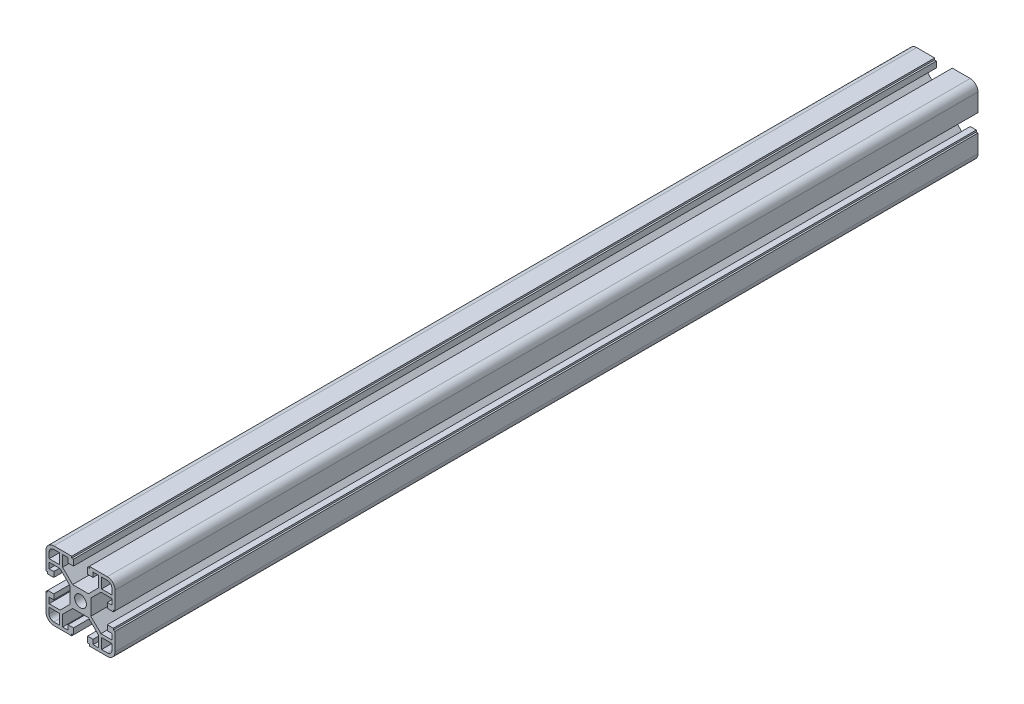
SolidWorks part; units mm, degrees
material "6063-T5"
ref_plane "Front Plane" through (0, 0, 0) normal (0, 0, 1) x (1, 0, 0)
ref_plane "Top Plane" through (0, 0, 0) normal (0, 1, 0) x (1, 0, 0)
ref_plane "Right Plane" through (0, 0, 0) normal (1, 0, 0) x (0, 0, -1)
sketch "Sketch3" plane through (0, 0, 0) normal (0, 0, 1) x (1, 0, 0)
  line L0 (17.9333, 92.7) -> (169.2667, 92.7) construction
  line L1 (-6, 6) -> (6, 6)
  line L2 (-6, 6) -> (-6, -6)
  line L3 (-6, -6) -> (6, -6)
  line L4 (6, 6) -> (6, -6)
  line L5 (0, 0) -> (20.1249, 20.1249) construction
  line L6 (4.5736, 4.5736) -> (11.4537, 11.4537) construction
  line L7 (5.2807, 3.8665) -> (12.0153, 10.6011)
  line L8 (3.8665, 5.2807) -> (10.7858, 12.2)
  line L13 (11.8142, 10.4) -> (18.2, 10.4)
  line L14 (6, 0) -> (23.1042, 0) construction
  line L15 (0, 6) -> (0, 13.9346) construction
  line L16 (4.5736, 4.5736) -> (11.8129, 11.8129) construction
  line L17 (5.2807, 3.8665) -> (12.52, 11.1058) construction
  line L18 (3.8665, 5.2807) -> (11.1058, 12.52) construction
  line L19 (10.4, 11.8142) -> (10.4, 18.2)
  line L20 (10.4, 18.2) -> (7.2581, 18.2)
  line L21 (-20, 20) -> (20, 20) construction
  line L22 (-20, 20) -> (-20, -20) construction
  line L23 (-20, -20) -> (20, -20) construction
  line L24 (20, 20) -> (20, -20) construction
  line L25 (7.2581, 18.2) -> (7.2581, 15.5)
  line L26 (7.2581, 15.5) -> (4.1, 15.5)
  line L27 (4.1, 15.5) -> (4.1, 19)
  line L28 (4.1, 19) -> (5.1, 19)
  line L29 (5.1, 19) -> (5.1, 20)
  line L30 (5.1, 20) -> (15.5, 20)
  line L31 (20, 15.5) -> (20, 5.1)
  line L32 (20, 5.1) -> (19, 5.1)
  line L33 (19, 5.1) -> (19, 4.1)
  line L34 (19, 4.1) -> (15.5, 4.1)
  line L35 (15.5, 4.1) -> (15.5, 7.1)
  line L36 (15.5, 7.1) -> (18.2, 7.1)
  line L37 (18.2, 7.1) -> (18.2, 10.4)
  line L42 (18.2, 12.2) -> (12.2, 12.2)
  line L43 (12.2, 18.2) -> (12.2, 18.2)
  line L44 (12.2, 18.2) -> (12.2, 18.2)
  line L45 (12.2, 18.2) -> (12.2, 18.2)
  line L46 (12.2, 18.2) -> (12.2, 18.2)
  line L47 (12.2, 18.2) -> (12.2, 18.2)
  line L48 (12.2, 18.2) -> (12.2, 18.2)
  line L49 (12.2, 18.2) -> (15.5, 18.2)
  line L50 (18.2, 15.5) -> (18.2, 12.2)
  line L51 (18.2, 12.2) -> (18.2, 12.2)
  line L52 (18.2, 12.2) -> (18.2, 12.2)
  line L53 (18.2, 12.2) -> (18.2, 12.2)
  line L54 (18.2, 12.2) -> (18.2, 12.2)
  line L55 (18.2, 12.2) -> (18.2, 12.2)
  line L56 (18.2, 12.2) -> (18.2, 12.2)
  line L57 (12.2, 12.2) -> (12.2, 18.2)
  line L58 (11.8142, 12.2) -> (18.2, 12.2) construction
  line L59 (12.2, 11.8142) -> (12.2, 18.2) construction
  line L60 (-18.2, 15.5) -> (-18.2, 12.2)
  line L61 (-12.2, 18.2) -> (-15.5, 18.2)
  line L62 (-12.2, 12.2) -> (-12.2, 18.2)
  line L63 (-18.2, 12.2) -> (-12.2, 12.2)
  line L64 (-11.8142, 10.4) -> (-18.2, 10.4)
  line L65 (-18.2, 7.1) -> (-18.2, 10.4)
  line L66 (-15.5, 7.1) -> (-18.2, 7.1)
  line L67 (-15.5, 4.1) -> (-15.5, 7.1)
  line L68 (-19, 4.1) -> (-15.5, 4.1)
  line L69 (-19, 5.1) -> (-19, 4.1)
  line L70 (-20, 5.1) -> (-19, 5.1)
  line L71 (-20, 15.5) -> (-20, 5.1)
  line L72 (-5.1, 20) -> (-15.5, 20)
  line L73 (-5.1, 19) -> (-5.1, 20)
  line L74 (-4.1, 19) -> (-5.1, 19)
  line L75 (-4.1, 15.5) -> (-4.1, 19)
  line L76 (-7.2581, 15.5) -> (-4.1, 15.5)
  line L77 (-7.2581, 18.2) -> (-7.2581, 15.5)
  line L78 (-10.4, 18.2) -> (-7.2581, 18.2)
  line L79 (-10.4, 11.8142) -> (-10.4, 18.2)
  line L80 (-10.4, 11.8142) -> (-4.5858, 6)
  line L81 (-11.8142, 10.4) -> (-6, 4.5858)
  line L82 (-18.2, -15.5) -> (-18.2, -12.2)
  line L83 (-18.2, -12.2) -> (-12.2, -12.2)
  line L84 (-12.2, -12.2) -> (-12.2, -18.2)
  line L85 (-12.2, -18.2) -> (-15.5, -18.2)
  line L86 (-20, -15.5) -> (-20, -5.1)
  line L87 (-20, -5.1) -> (-19, -5.1)
  line L88 (-19, -5.1) -> (-19, -4.1)
  line L89 (-19, -4.1) -> (-15.5, -4.1)
  line L90 (-15.5, -4.1) -> (-15.5, -7.1)
  line L91 (-15.5, -7.1) -> (-18.2, -7.1)
  line L92 (-18.2, -7.1) -> (-18.2, -10.4)
  line L93 (-11.8142, -10.4) -> (-18.2, -10.4)
  line L94 (-11.8142, -10.4) -> (-6, -4.5858)
  line L95 (-10.4, -11.8142) -> (-4.5858, -6)
  line L96 (-10.4, -11.8142) -> (-10.4, -18.2)
  line L97 (-10.4, -18.2) -> (-7.2581, -18.2)
  line L98 (-7.2581, -18.2) -> (-7.2581, -15.5)
  line L99 (-7.2581, -15.5) -> (-4.1, -15.5)
  line L100 (-4.1, -15.5) -> (-4.1, -19)
  line L101 (-4.1, -19) -> (-5.1, -19)
  line L102 (-5.1, -19) -> (-5.1, -20)
  line L103 (-5.1, -20) -> (-15.5, -20)
  line L104 (12.2, -18.2) -> (15.5, -18.2)
  line L105 (12.2, -12.2) -> (12.2, -18.2)
  line L106 (18.2, -12.2) -> (12.2, -12.2)
  line L107 (18.2, -15.5) -> (18.2, -12.2)
  line L108 (5.1, -20) -> (15.5, -20)
  line L109 (5.1, -19) -> (5.1, -20)
  line L110 (4.1, -19) -> (5.1, -19)
  line L111 (4.1, -15.5) -> (4.1, -19)
  line L112 (7.2581, -15.5) -> (4.1, -15.5)
  line L113 (10.4, -18.2) -> (7.2581, -18.2)
  line L114 (7.2581, -18.2) -> (7.2581, -15.5)
  line L115 (10.4, -11.8142) -> (10.4, -18.2)
  line L116 (10.4, -11.8142) -> (4.5858, -6)
  line L117 (11.8142, -10.4) -> (6, -4.5858)
  line L118 (11.8142, -10.4) -> (18.2, -10.4)
  line L119 (18.2, -7.1) -> (18.2, -10.4)
  line L120 (20, -15.5) -> (20, -5.1)
  line L121 (20, -5.1) -> (19, -5.1)
  line L122 (19, -5.1) -> (19, -4.1)
  line L123 (15.5, -7.1) -> (18.2, -7.1)
  line L124 (15.5, -4.1) -> (15.5, -7.1)
  line L125 (19, -4.1) -> (15.5, -4.1)
  circle A0 centre (0, 0) radius 3.4
  arc A1 (15.5, 20) -> (20, 15.5) centre (15.5, 15.5) cw
  arc A2 (15.5, 18.2) -> (18.2, 15.5) centre (15.5, 15.5) cw
  arc A3 (-15.5, 18.2) -> (-18.2, 15.5) centre (-15.5, 15.5) ccw
  arc A4 (-15.5, 20) -> (-20, 15.5) centre (-15.5, 15.5) ccw
  arc A5 (-15.5, -18.2) -> (-18.2, -15.5) centre (-15.5, -15.5) cw
  arc A6 (-15.5, -20) -> (-20, -15.5) centre (-15.5, -15.5) cw
  arc A7 (15.5, -18.2) -> (18.2, -15.5) centre (15.5, -15.5) ccw
  arc A8 (15.5, -20) -> (20, -15.5) centre (15.5, -15.5) ccw
  point P7 (6, 0)
  point P8 (0, 6)
  point P36 (0, 20)
  point P37 (-20, 0)
  dimension "D3" = 6.8
  dimension "D28" = 4.5
  dimension "D1" = 12
  dimension "D2" = 12
  dimension "D6" = 10.4
  dimension "D7" = 10.4
  dimension "D8" = 40
  dimension "D9" = 40
  dimension "D10" = 1
  dimension "D11" = 1
  dimension "D12" = 1.8
  dimension "D13" = 1.8
  dimension "D14" = 2
  dimension "D17" = 1.8
  dimension "D18" = 1.8
  dimension "D19" = 1
  dimension "D20" = 1
  dimension "D21" = 3.5
  dimension "D22" = 5.1
  dimension "D23" = 4.1
  dimension "D24" = 3
  dimension "D25" = 3.5
  dimension "D26" = 4.1
  dimension "D27" = 5.1
  dimension "D4" = 1
  dimension "D5" = 1
  dimension "D29" = 1.8
extrude "Boss-Extrude1" add sketch "Sketch3" along normal blind 500
